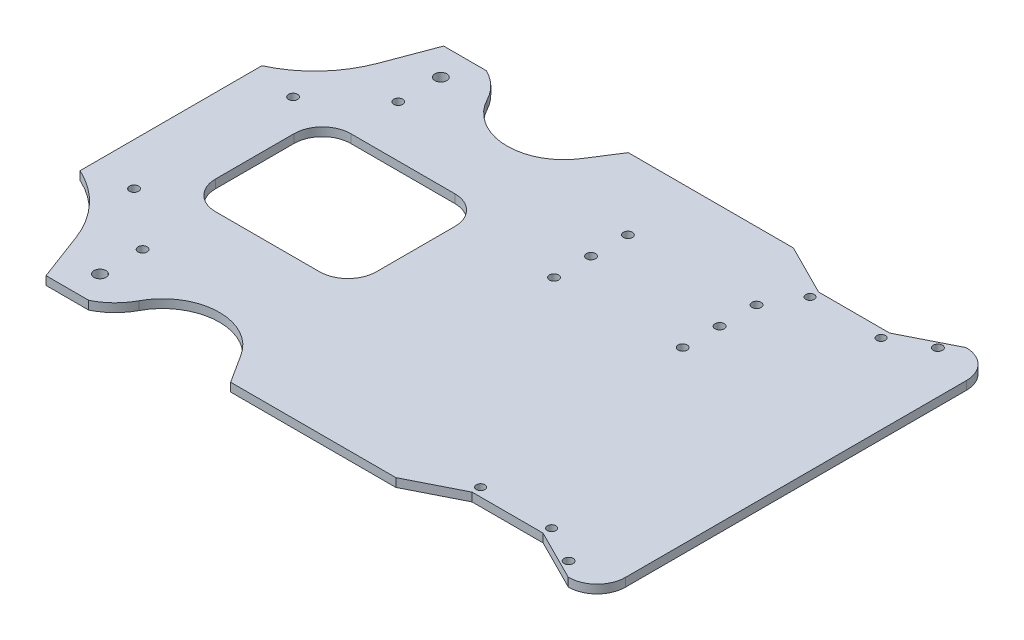
SolidWorks part; units mm, degrees
ref_plane "Front Plane" through (0, 0, 0) normal (0, 0, 1) x (1, 0, 0)
ref_plane "Top Plane" through (0, 0, 0) normal (0, 1, 0) x (1, 0, 0)
ref_plane "Right Plane" through (0, 0, 0) normal (1, 0, 0) x (0, 0, -1)
sketch "Çizim16" plane through (0, 0, 0) normal (0, 1, 0) x (1, 0, 0)
  line L1 (-110, -70) -> (100, -70)
  line L2 (-110, -70) -> (-110, 70)
  line L3 (-110, 70) -> (100, 70)
  line L4 (110, -60) -> (110, 60)
  line L5 (-110, -70) -> (110, 70) construction
  line L6 (-110, 70) -> (110, -70) construction
  arc A0 (100, -70) -> (110, -60) centre (100, -60) ccw
  arc A1 (100, 70) -> (110, 60) centre (100, 60) cw
  point P0 (0, 0)
  dimension "D3" = 10
  dimension "D1" = 220
  dimension "D2" = 140
extrude "Yükseklik-Ekstrüzyon3" add sketch "Çizim16" along normal blind 3
sketch "Çizim18" plane through (0, 3, 0) normal (0, 1, 0) x (1, 0, 0)
  line L0 (-19, 70) -> (-25.4638, 59.8897)
  line L1 (100, 70) -> (-110, 70) construction
  line L2 (-69, 70) -> (-19, 70)
  line L3 (-110, 70) -> (-110, -70) construction
  arc A0 (-25.4638, 59.8897) -> (-60, 61.3236) centre (-42.3144, 70.6627) cw
  arc A1 (-60, 61.3236) -> (-69, 70) centre (-77.6856, 51.9844) ccw
  dimension "D3" = 20
  dimension "D4" = 20
  dimension "D1" = 50
  dimension "D2" = 12
  dimension "D5" = 41
  dimension "D6" = 50
extrude "Kes-Ekstrüzyon10" cut sketch "Çizim18" against normal blind 3
sketch "Çizim19" plane through (0, 3, 0) normal (0, 1, 0) x (1, 0, 0)
  line L0 (-19, -70) -> (-25.4638, -59.8897)
  line L1 (-110, -70) -> (100, -70) construction
  line L2 (-69, -70) -> (-19, -70)
  line L3 (-110, 70) -> (-110, -70) construction
  arc A0 (-25.4638, -59.8897) -> (-60, -61.3236) centre (-42.3144, -70.6627) ccw
  arc A1 (-60, -61.3236) -> (-69, -70) centre (-77.6856, -51.9844) cw
  dimension "D1" = 20
  dimension "D3" = 20
  dimension "D2" = 12
  dimension "D4" = 50
  dimension "D5" = 41
  dimension "D6" = 50
extrude "Kes-Ekstrüzyon11" cut sketch "Çizim19" against normal blind 3
sketch "Çizim23" plane through (0, 3, 0) normal (0, 1, 0) x (1, 0, 0)
  line L0 (-84, -70) -> (-90.3297, -53.1496)
  line L1 (-110, -70) -> (-69, -70) construction
  line L2 (-110, 70) -> (-110, -70) construction
  line L3 (-110, -32) -> (-110, -70)
  line L4 (-110, -70) -> (-84, -70)
  arc A0 (-90.3297, -53.1496) -> (-110, -32) centre (-125.9027, -66.5124) ccw
  dimension "D2" = 38
  dimension "D1" = 18
  dimension "D3" = 38
  dimension "D4" = 26
extrude "Kes-Ekstrüzyon14" cut sketch "Çizim23" against normal blind 3
sketch "Çizim24" plane through (0, 3, 0) normal (0, 1, 0) x (1, 0, 0)
  line L0 (-84, 70) -> (-90.3297, 53.1496)
  line L1 (-69, 70) -> (-110, 70) construction
  line L2 (-110, 70) -> (-110, -32) construction
  line L3 (-110, 32) -> (-110, 70)
  line L4 (-110, 70) -> (-84, 70)
  arc A0 (-90.3297, 53.1496) -> (-110, 32) centre (-125.9027, 66.5124) cw
  dimension "D3" = 38
  dimension "D1" = 26
  dimension "D2" = 38
  dimension "D4" = 18
extrude "Kes-Ekstrüzyon15" cut sketch "Çizim24" against normal blind 3
sketch "Çizim25" plane through (0, 3, 0) normal (0, 1, 0) x (1, 0, 0)
  line L1 (-84, -70) -> (-69, -70) construction
  line L2 (-110, 32) -> (-110, -32) construction
  line L3 (-69, 70) -> (-84, 70) construction
  circle A0 centre (-95, 28) radius 1.6
  circle A1 centre (-95, -28) radius 1.6
  dimension "D1" = 3.2
  dimension "D2" = 3.2
  dimension "D3" = 42
  dimension "D5" = 15
  dimension "D4" = 42
  dimension "D6" = 15
extrude "Kes-Ekstrüzyon16" cut sketch "Çizim25" against normal blind 10
sketch "Çizim33" plane through (0, 3, 0) normal (0, 1, 0) x (1, 0, 0)
  line L0 (-84, -70) -> (-69, -70) construction
  line L1 (-110, 32) -> (-110, -32) construction
  line L2 (-69, 70) -> (-84, 70) construction
  circle A0 centre (-75, -60) radius 2.1
  circle A1 centre (-75, 60) radius 2.1
  circle A2 centre (-75, 45) radius 1.6
  circle A3 centre (-75, -45) radius 1.6
  dimension "D1" = 4.2
  dimension "D2" = 4.2
  dimension "D3" = 10
  dimension "D4" = 35
  dimension "D5" = 35
  dimension "D6" = 10
  dimension "D7" = 3.2
  dimension "D8" = 3.2
  dimension "D9" = 15
  dimension "D10" = 0
  dimension "D11" = 0
  dimension "D12" = 15
extrude "Kes-Ekstrüzyon18" cut sketch "Çizim33" against normal blind 3
sketch "Çizim34" plane through (0, 3, 0) normal (0, 1, 0) x (1, 0, 0)
  line L0 (-19, -70) -> (100, -70) construction
  line L1 (110, -60) -> (110, 60) construction
  line L2 (100, 70) -> (-19, 70) construction
  circle A0 centre (95, -65) radius 1.6
  circle A1 centre (95, 65) radius 1.6
  dimension "D1" = 3.2
  dimension "D2" = 3.2
  dimension "D3" = 5
  dimension "D4" = 15
  dimension "D5" = 15
  dimension "D6" = 5
extrude "Kes-Ekstrüzyon19" cut sketch "Çizim34" against normal blind 10
sketch "Çizim37" plane through (0, 3, 0) normal (0, 1, 0) x (1, 0, 0)
  line L1 (-73.629, -20.666) -> (-37.0186, -20.666)
  line L2 (-83.629, -10.666) -> (-83.629, 16.9382)
  line L3 (-73.629, 26.9382) -> (-37.0186, 26.9382)
  line L4 (-27.0186, -10.666) -> (-27.0186, 16.9382)
  line L5 (-83.629, -20.666) -> (-27.0186, 26.9382) construction
  line L6 (-83.629, 26.9382) -> (-27.0186, -20.666) construction
  arc A0 (-37.0186, -20.666) -> (-27.0186, -10.666) centre (-37.0186, -10.666) ccw
  arc A1 (-37.0186, 26.9382) -> (-27.0186, 16.9382) centre (-37.0186, 16.9382) cw
  arc A2 (-73.629, -20.666) -> (-83.629, -10.666) centre (-73.629, -10.666) cw
  arc A3 (-83.629, 16.9382) -> (-73.629, 26.9382) centre (-73.629, 16.9382) cw
  point P0 (-55.3238, 3.1361)
  dimension "D1" = 10
extrude "Kes-Ekstrüzyon21" cut sketch "Çizim37" against normal blind 10
sketch "Çizim38" plane through (0, 3, 0) normal (0, 1, 0) x (1, 0, 0)
  line L0 (-19, -70) -> (100, -70) construction
  line L1 (110, -60) -> (110, 60) construction
  line L2 (100, 70) -> (-19, 70) construction
  circle A0 centre (57, -58) radius 1.5
  circle A1 centre (82, -58) radius 1.5
  circle A2 centre (57, 58) radius 1.5
  circle A3 centre (82, 58) radius 1.5
  dimension "D1" = 3
  dimension "D2" = 3
  dimension "D3" = 12
  dimension "D4" = 12
  dimension "D5" = 28
  dimension "D6" = 25
  dimension "D7" = 3
  dimension "D8" = 3
  dimension "D9" = 25
  dimension "D10" = 28
  dimension "D11" = 12
  dimension "D12" = 12
extrude "Kes-Ekstrüzyon22" cut sketch "Çizim38" against normal blind 10
sketch "Çizim39" plane through (0, 3, 0) normal (0, 1, 0) x (1, 0, 0)
  line L0 (-19, -70) -> (100, -70) construction
  line L1 (82, -61) -> (57, -61)
  line L2 (82, -61) -> (82, -70)
  line L3 (82, -70) -> (57, -70)
  line L4 (57, -61) -> (57, -70)
  line L5 (110, -60) -> (110, 60) construction
  line L6 (100, 70) -> (-19, 70) construction
  line L7 (82, 70) -> (57, 70)
  line L8 (82, 70) -> (82, 61)
  line L9 (82, 61) -> (57, 61)
  line L10 (57, 70) -> (57, 61)
  line L11 (82, -61) -> (99.8606, -70)
  line L12 (99.8606, -70) -> (82, -70)
  line L13 (57, -61) -> (39.1394, -70)
  line L14 (39.1394, -70) -> (57, -70)
  line L15 (57, 61) -> (39.1394, 70)
  line L16 (39.1394, 70) -> (57, 70)
  line L17 (82, 61) -> (99.8606, 70)
  line L18 (99.8606, 70) -> (82, 70)
  line M31 (-19, -70) -> (100, -70)
  line M35 (100, 70) -> (-19, 70)
  dimension "D1" = 25
  dimension "D2" = 9
  dimension "D3" = 28
  dimension "D4" = 25
  dimension "D5" = 9
  dimension "D6" = 28
  dimension "D7" = 20
  dimension "D8" = 20
  dimension "D9" = 20
  dimension "D10" = 20
extrude "Kes-Ekstrüzyon23" cut sketch "Çizim39" against normal blind 10 contours L1 L4 L2 M31 | L4 L13 M31 | L11 L2 M31 | L15 L10 M35 | L10 L9 L8 M35 | L8 L17 M35
sketch "Çizim40" plane through (0, 3, 0) normal (0, 1, 0) x (-1, 0, 0)
  line L0 (-110, 60) -> (-110, -60) construction
  circle A0 centre (-6, -44.857) radius 1.6
  circle A1 centre (-50, -46.1444) radius 1.6
  circle A2 centre (-50, -33.1444) radius 1.6
  circle A3 centre (-6, -31.857) radius 1.6
  circle A4 centre (-50, -20.1444) radius 1.6
  circle A5 centre (-6, -18.857) radius 1.6
  dimension "D1" = 3.2
  dimension "D2" = 3.2
  dimension "D3" = 44
  dimension "D4" = 60
  dimension "D5" = 3.2
  dimension "D6" = 3.2
  dimension "D7" = 3.2
  dimension "D8" = 3.2
  dimension "D9" = 13
  dimension "D10" = 60
  dimension "D11" = 60
  dimension "D12" = 13
  dimension "D13" = 44
  dimension "D14" = 13
  dimension "D15" = 44
  dimension "D16" = 13
extrude "Kes-Ekstrüzyon24" cut sketch "Çizim40" against normal blind 100
